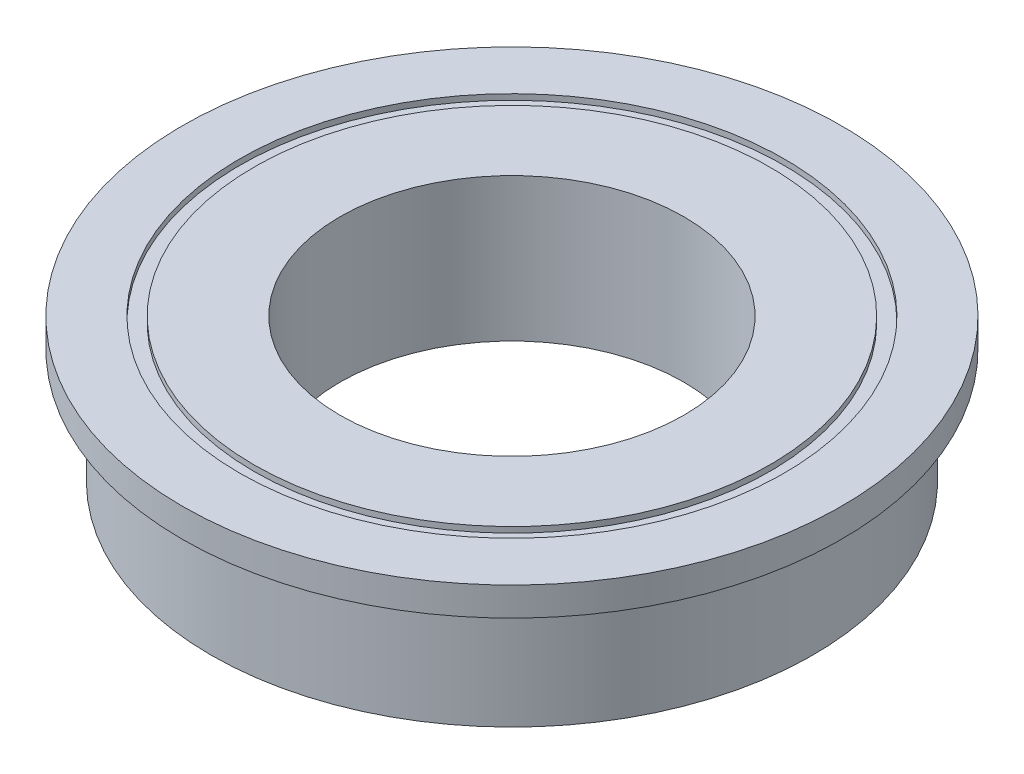
SolidWorks part; units mm, degrees
ref_plane "前视基准面" through (0, 0, 0) normal (0, 0, 1) x (1, 0, 0)
ref_plane "上视基准面" through (0, 0, 0) normal (0, 1, 0) x (1, 0, 0)
ref_plane "右视基准面" through (0, 0, 0) normal (1, 0, 0) x (0, 0, -1)
sketch "草图1" plane through (0, 0, 0) normal (0, 1, 0) x (1, 0, 0)
  circle A0 centre (0, 0) radius 6
  circle A1 centre (0, 0) radius 10.5
  dimension "D1" = 12
  dimension "D2" = 21
extrude "凸台-拉伸1" add sketch "草图1" along normal blind 4
sketch "草图2" plane through (0, 4, 0) normal (0, 1, 0) x (1, 0, 0)
  circle A0 centre (0, 0) radius 6
  circle A1 centre (0, 0) radius 11.5
  dimension "D1" = 23
extrude "凸台-拉伸2" add sketch "草图2" along normal blind 1
sketch "草图3" plane through (0, 0, 0) normal (0, -1, 0) x (1, 0, 0)
  circle A0 centre (0, 0) radius 9.5
  circle A1 centre (0, 0) radius 9
  dimension "D1" = 19
  dimension "D2" = 18
extrude "切除-拉伸1" cut sketch "草图3" against normal blind 0.2
sketch "草图4" plane through (0, 5, 0) normal (0, 1, 0) x (1, 0, 0)
  circle A0 centre (0, 0) radius 9.5 construction
  circle A1 centre (0, 0) radius 9 construction
  circle A2 centre (0, 0) radius 9.5
  circle A3 centre (0, 0) radius 9
extrude "切除-拉伸2" cut sketch "草图4" against normal blind 0.2
